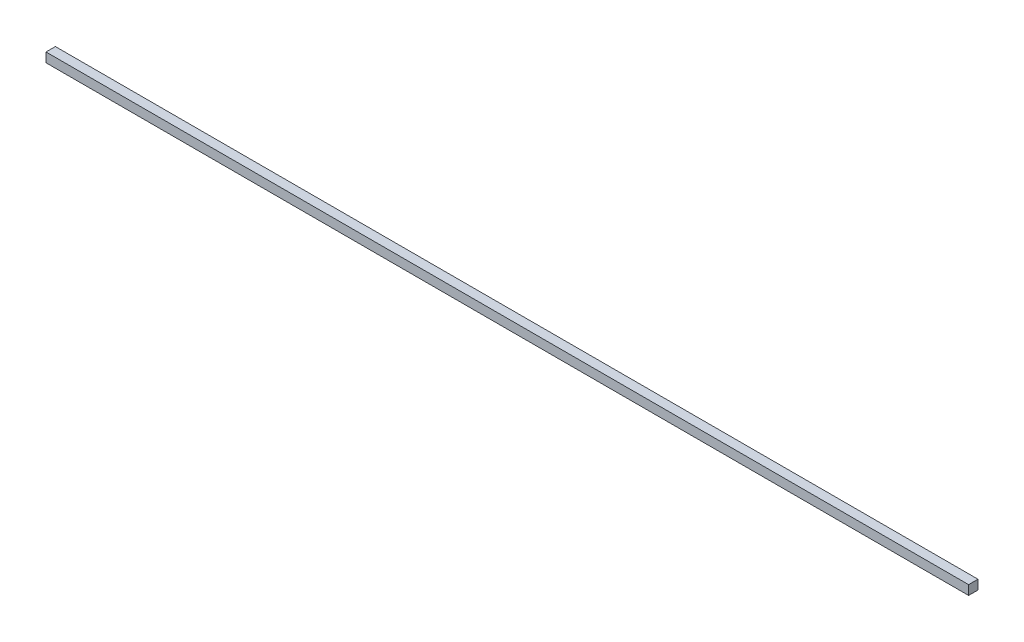
SolidWorks part; units mm, degrees
material "Balsa"
ref_plane "Front Plane" through (0, 0, 0) normal (0, 0, 1) x (1, 0, 0)
ref_plane "Top Plane" through (0, 0, 0) normal (0, 1, 0) x (1, 0, 0)
ref_plane "Right Plane" through (0, 0, 0) normal (1, 0, 0) x (0, 0, -1)
sketch "Sketch1" plane through (0, 0, 0) normal (1, 0, 0) x (0, 0, -1)
  line L1 (-1.5875, 1.5875) -> (1.5875, 1.5875)
  line L2 (-1.5875, 1.5875) -> (-1.5875, -1.5875)
  line L3 (-1.5875, -1.5875) -> (1.5875, -1.5875)
  line L4 (1.5875, 1.5875) -> (1.5875, -1.5875)
  line L5 (-1.5875, 1.5875) -> (1.5875, -1.5875) construction
  line L6 (-1.5875, -1.5875) -> (1.5875, 1.5875) construction
  point P0 (0, 0)
  dimension "D1" = 3.175
extrude "Boss-Extrude1" add sketch "Sketch1" along normal blind 312.1
